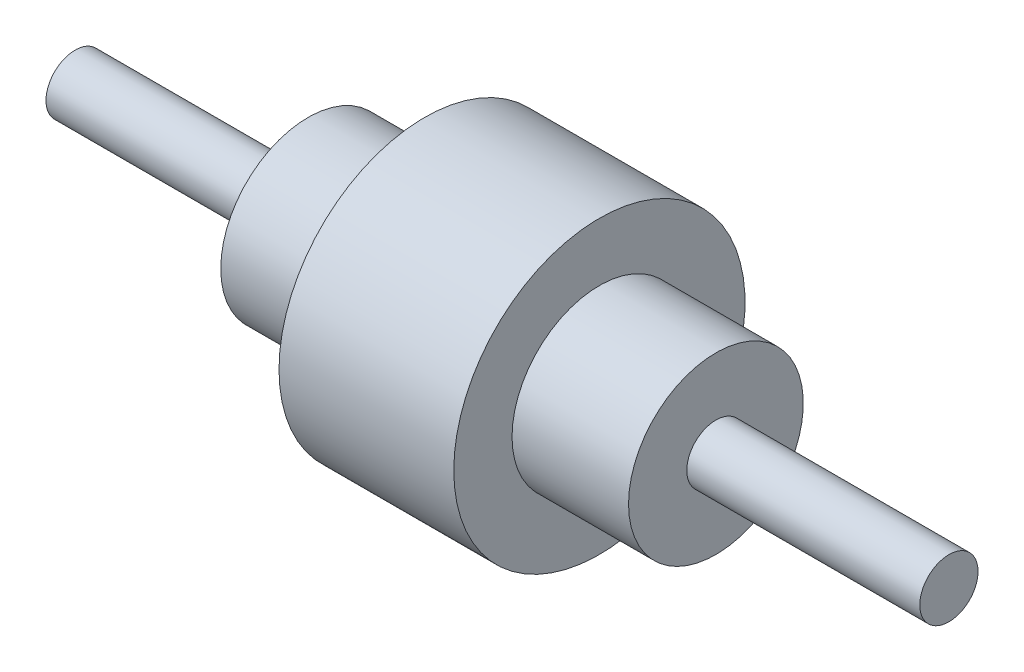
SolidWorks part; units mm, degrees
ref_plane "前基準面" through (0, 0, 0) normal (0, 0, 1) x (1, 0, 0)
ref_plane "上基準面" through (0, 0, 0) normal (0, 1, 0) x (1, 0, 0)
ref_plane "右基準面" through (0, 0, 0) normal (1, 0, 0) x (0, 0, -1)
sketch "草圖1" plane through (0, 0, 0) normal (0, 0, 1) x (1, 0, 0)
  line L0 (0, 0) -> (51.2726, 0) construction
  line L1 (80, 10) -> (80, 30)
  line L2 (0, 0) -> (80, 0)
  line L3 (0, 0) -> (0, 10)
  line L4 (0, 10) -> (80, 10)
  line L5 (80, 0) -> (80, 10)
  line L6 (80, 30) -> (120, 30)
  line L7 (120, 30) -> (120, 0)
  line L8 (120, 30) -> (120, 50)
  line L9 (120, 50) -> (180, 50)
  line L10 (180, 50) -> (180, 0)
  line L11 (180, 30) -> (220, 30)
  line L12 (220, 30) -> (220, 0)
  line L15 (220, 10) -> (300, 10)
  line L16 (300, 10) -> (300, 0)
  line L17 (300, 0) -> (0, 0)
  point P14 (0, 0)
  dimension "D1" = 10
  dimension "D2" = 30
  dimension "D3" = 50
  dimension "D4" = 30
  dimension "D5" = 10
  dimension "D6" = 80
  dimension "D7" = 300
  dimension "D8" = 80
  dimension "D9" = 40
  dimension "D10" = 40
revolve "旋轉1" add sketch "草圖1" angle 360 about L0
